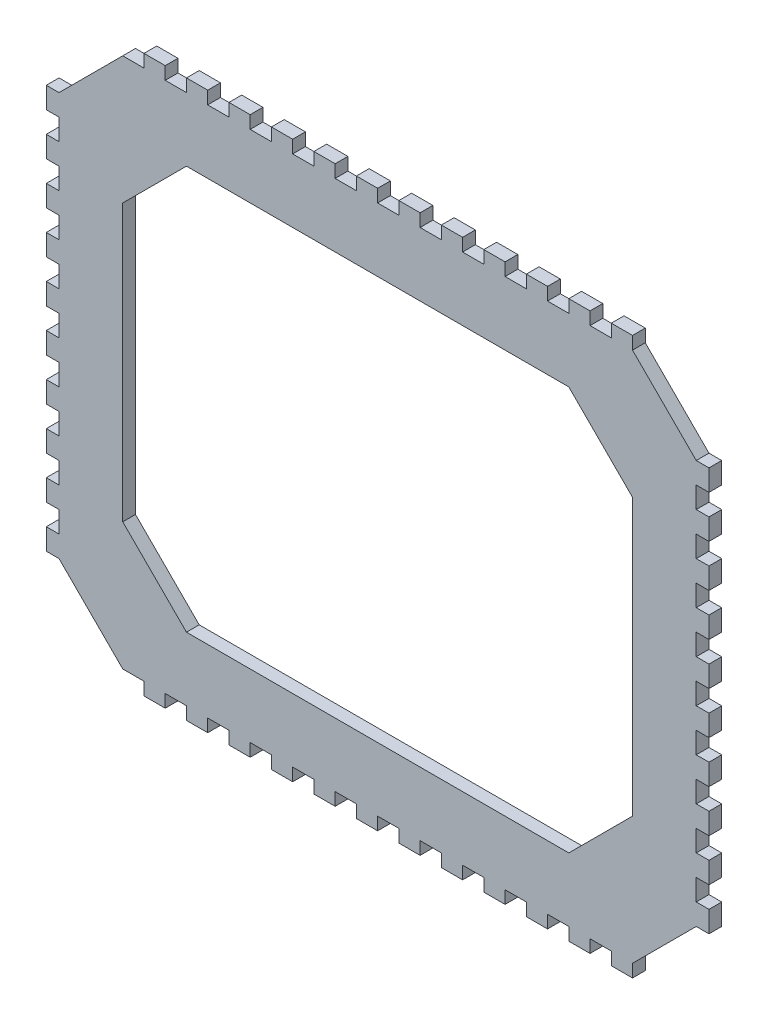
SolidWorks part; units mm, degrees
material "Buche"
ref_plane "Ebene vorne" through (0, 0, 0) normal (0, 0, 1) x (1, 0, 0)
ref_plane "Ebene oben" through (0, 0, 0) normal (0, 1, 0) x (1, 0, 0)
ref_plane "Ebene rechts" through (0, 0, 0) normal (1, 0, 0) x (0, 0, -1)
sketch "Skizze1" plane through (0, 0, 0) normal (0, 0, 1) x (1, 0, 0)
  line L0 (30, 0) -> (0, 30)
  line L1 (50, 0) -> (60, 0)
  line L2 (0, 50) -> (-6, 50)
  line L3 (30, 250) -> (40, 250)
  line L4 (300, 30) -> (306, 30)
  line L5 (270, 0) -> (300, 30)
  line L6 (0, 220) -> (30, 250)
  line L7 (300, 220) -> (270, 250)
  line L8 (30, 190) -> (60, 220)
  line L9 (60, 30) -> (240, 30)
  line L10 (30, 60) -> (30, 190)
  line L11 (60, 220) -> (240, 220)
  line L12 (270, 60) -> (270, 190)
  line L13 (270, 190) -> (240, 220)
  line L14 (240, 30) -> (270, 60)
  line L15 (60, 30) -> (30, 60)
  line L16 (30, 0) -> (40, 0)
  line L17 (40, 0) -> (40, -6)
  line L18 (40, -6) -> (50, -6)
  line L19 (50, -6) -> (50, 0)
  line L20 (60, 0) -> (60, -6)
  line L21 (60, -6) -> (70, -6)
  line L22 (70, -6) -> (70, 0)
  line L23 (70, 0) -> (80, 0)
  line L24 (80, 0) -> (80, -6)
  line L25 (80, -6) -> (90, -6)
  line L26 (90, -6) -> (90, 0)
  line L27 (90, 0) -> (100, 0)
  line L28 (100, 0) -> (100, -6)
  line L29 (100, -6) -> (110, -6)
  line L30 (110, -6) -> (110, 0)
  line L31 (110, 0) -> (120, 0)
  line L32 (120, 0) -> (120, -6)
  line L33 (120, -6) -> (130, -6)
  line L34 (130, -6) -> (130, 0)
  line L35 (130, 0) -> (140, 0)
  line L36 (140, 0) -> (140, -6)
  line L37 (140, -6) -> (150, -6)
  line L38 (150, -6) -> (150, 0)
  line L39 (150, 0) -> (160, 0)
  line L40 (160, 0) -> (160, -6)
  line L41 (160, -6) -> (170, -6)
  line L42 (170, -6) -> (170, 0)
  line L43 (170, 0) -> (180, 0)
  line L44 (180, 0) -> (180, -6)
  line L45 (180, -6) -> (190, -6)
  line L46 (190, -6) -> (190, 0)
  line L47 (190, 0) -> (200, 0)
  line L48 (200, 0) -> (200, -6)
  line L49 (200, -6) -> (210, -6)
  line L50 (210, -6) -> (210, 0)
  line L51 (210, 0) -> (220, 0)
  line L52 (220, 0) -> (220, -6)
  line L53 (220, -6) -> (230, -6)
  line L54 (230, -6) -> (230, 0)
  line L55 (230, 0) -> (240, 0)
  line L56 (240, 0) -> (240, -6)
  line L57 (240, -6) -> (250, -6)
  line L58 (250, -6) -> (250, 0)
  line L59 (250, 0) -> (260, 0)
  line L60 (260, 0) -> (260, -6)
  line L61 (260, -6) -> (270, -6)
  line L62 (270, -6) -> (270, 0)
  line L63 (0, 30) -> (-6, 30)
  line L64 (-6, 30) -> (-6, 40)
  line L65 (-6, 40) -> (0, 40)
  line L66 (0, 40) -> (0, 50)
  line L67 (-6, 50) -> (-6, 60)
  line L68 (-6, 60) -> (0, 60)
  line L69 (0, 60) -> (0, 70)
  line L70 (0, 70) -> (-6, 70)
  line L71 (-6, 70) -> (-6, 80)
  line L72 (-6, 80) -> (0, 80)
  line L73 (0, 80) -> (0, 90)
  line L74 (0, 90) -> (-6, 90)
  line L75 (-6, 90) -> (-6, 100)
  line L76 (-6, 100) -> (0, 100)
  line L77 (0, 100) -> (0, 110)
  line L78 (0, 110) -> (-6, 110)
  line L79 (-6, 110) -> (-6, 120)
  line L80 (-6, 120) -> (0, 120)
  line L81 (0, 120) -> (0, 130)
  line L82 (0, 130) -> (-6, 130)
  line L83 (-6, 130) -> (-6, 140)
  line L84 (-6, 140) -> (0, 140)
  line L85 (0, 140) -> (0, 150)
  line L86 (0, 150) -> (-6, 150)
  line L87 (-6, 150) -> (-6, 160)
  line L88 (-6, 160) -> (0, 160)
  line L89 (0, 160) -> (0, 170)
  line L90 (0, 170) -> (-6, 170)
  line L91 (-6, 170) -> (-6, 180)
  line L92 (-6, 180) -> (0, 180)
  line L93 (0, 180) -> (0, 190)
  line L94 (0, 190) -> (-6, 190)
  line L95 (-6, 190) -> (-6, 200)
  line L96 (-6, 200) -> (0, 200)
  line L97 (0, 200) -> (0, 210)
  line L98 (0, 210) -> (-6, 210)
  line L99 (-6, 210) -> (-6, 220)
  line L100 (-6, 220) -> (0, 220)
  line L101 (306, 30) -> (306, 40)
  line L102 (0, 220) -> (0, 230) [skipped]
  line L103 (306, 40) -> (300, 40)
  line L104 (300, 40) -> (300, 50)
  line L105 (300, 50) -> (306, 50)
  line L106 (306, 50) -> (306, 60)
  line L107 (306, 60) -> (300, 60)
  line L108 (300, 60) -> (300, 70)
  line L109 (300, 70) -> (306, 70)
  line L110 (306, 70) -> (306, 80)
  line L111 (306, 80) -> (300, 80)
  line L112 (300, 80) -> (300, 90)
  line L113 (300, 90) -> (306, 90)
  line L114 (306, 90) -> (306, 100)
  line L115 (306, 100) -> (300, 100)
  line L116 (300, 100) -> (300, 110)
  line L117 (300, 110) -> (306, 110)
  line L118 (306, 110) -> (306, 120)
  line L119 (306, 120) -> (300, 120)
  line L120 (300, 120) -> (300, 130)
  line L121 (300, 130) -> (306, 130)
  line L122 (306, 130) -> (306, 140)
  line L123 (306, 140) -> (300, 140)
  line L124 (300, 140) -> (300, 150)
  line L125 (300, 150) -> (306, 150)
  line L126 (306, 150) -> (306, 160)
  line L127 (306, 160) -> (300, 160)
  line L128 (300, 160) -> (300, 170)
  line L129 (300, 170) -> (306, 170)
  line L130 (306, 170) -> (306, 180)
  line L131 (306, 180) -> (300, 180)
  line L132 (300, 180) -> (300, 190)
  line L133 (300, 190) -> (306, 190)
  line L134 (306, 190) -> (306, 200)
  line L135 (306, 200) -> (300, 200)
  line L136 (300, 200) -> (300, 210)
  line L137 (300, 210) -> (306, 210)
  line L138 (306, 210) -> (306, 220)
  line L139 (306, 220) -> (300, 220)
  line L140 (40, 250) -> (40, 256)
  line L141 (300, 220) -> (300, 230) [skipped]
  line L142 (40, 256) -> (50, 256)
  line L143 (50, 256) -> (50, 250)
  line L144 (50, 250) -> (60, 250)
  line L145 (60, 250) -> (60, 256)
  line L146 (60, 256) -> (70, 256)
  line L147 (70, 256) -> (70, 250)
  line L148 (70, 250) -> (80, 250)
  line L149 (80, 250) -> (80, 256)
  line L150 (80, 256) -> (90, 256)
  line L151 (90, 256) -> (90, 250)
  line L152 (90, 250) -> (100, 250)
  line L153 (100, 250) -> (100, 256)
  line L154 (100, 256) -> (110, 256)
  line L155 (110, 256) -> (110, 250)
  line L156 (110, 250) -> (120, 250)
  line L157 (120, 250) -> (120, 256)
  line L158 (120, 256) -> (130, 256)
  line L159 (130, 256) -> (130, 250)
  line L160 (130, 250) -> (140, 250)
  line L161 (140, 250) -> (140, 256)
  line L162 (140, 256) -> (150, 256)
  line L163 (150, 256) -> (150, 250)
  line L164 (150, 250) -> (160, 250)
  line L165 (160, 250) -> (160, 256)
  line L166 (160, 256) -> (170, 256)
  line L167 (170, 256) -> (170, 250)
  line L168 (170, 250) -> (180, 250)
  line L169 (180, 250) -> (180, 256)
  line L170 (180, 256) -> (190, 256)
  line L171 (190, 256) -> (190, 250)
  line L172 (190, 250) -> (200, 250)
  line L173 (200, 250) -> (200, 256)
  line L174 (200, 256) -> (210, 256)
  line L175 (210, 256) -> (210, 250)
  line L176 (210, 250) -> (220, 250)
  line L177 (220, 250) -> (220, 256)
  line L178 (220, 256) -> (230, 256)
  line L179 (230, 256) -> (230, 250)
  line L180 (230, 250) -> (240, 250)
  line L181 (240, 250) -> (240, 256)
  line L182 (240, 256) -> (250, 256)
  line L183 (250, 256) -> (250, 250)
  line L184 (250, 250) -> (260, 250)
  line L185 (260, 250) -> (260, 256)
  line L186 (260, 256) -> (270, 256)
  line L187 (270, 256) -> (270, 250)
  dimension "D1" = 12
  dimension "D2" = 10
  dimension "D3" = 10
  dimension "D4" = 12
  dimension "D5" = 6
  dimension "D6" = 6
  dimension "D7" = 6
  dimension "D8" = 6
  dimension "D9" = 312
extrude "Aufsatz-Linear austragen2" add sketch "Skizze1" along normal blind 6
